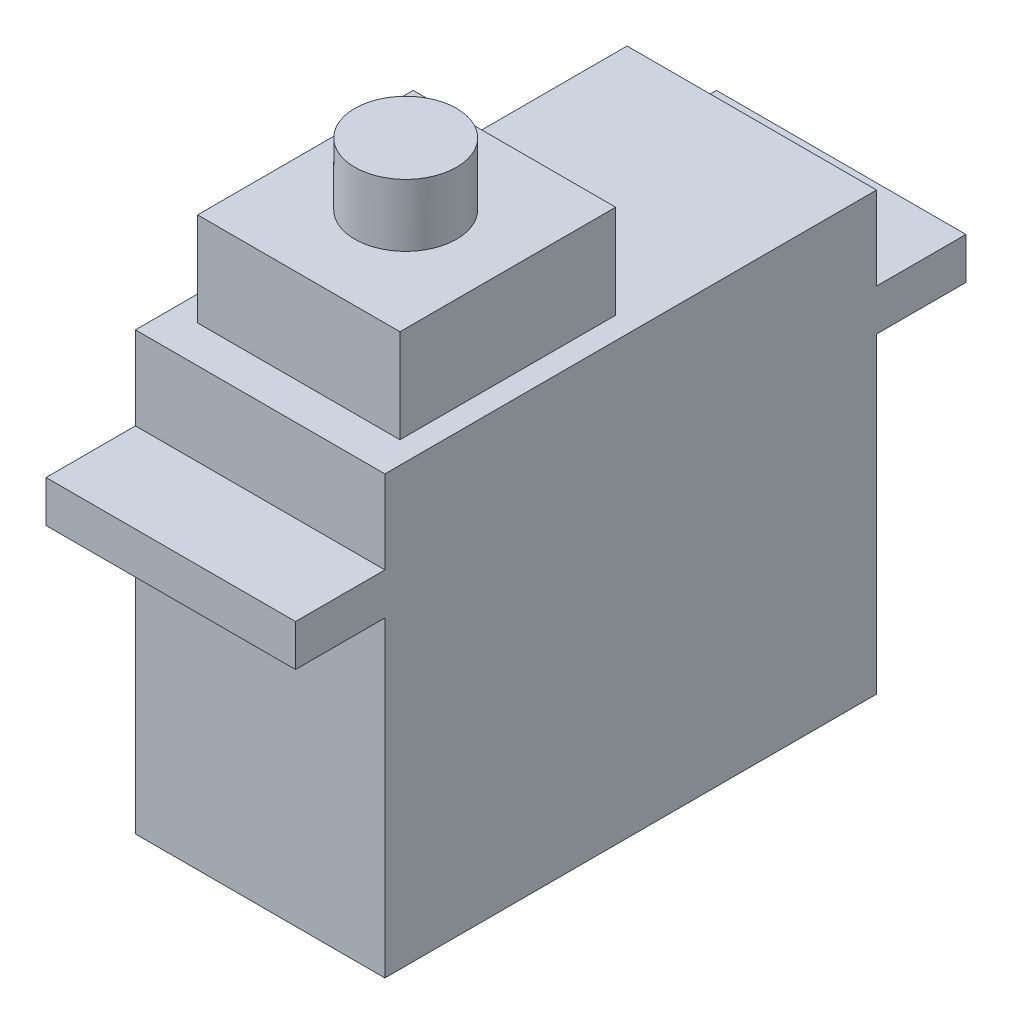
SolidWorks part; units mm, degrees
ref_plane "Front Plane" through (0, 0, 0) normal (0, 0, 1) x (1, 0, 0)
ref_plane "Top Plane" through (0, 0, 0) normal (0, 1, 0) x (1, 0, 0)
ref_plane "Right Plane" through (0, 0, 0) normal (1, 0, 0) x (0, 0, -1)
sketch "Sketch1" plane through (0, 0, 0) normal (1, 0, 0) x (0, 0, -1)
  line L0 (-11.825, 6.5) -> (-11.825, 10.5)
  line L1 (-11.825, -10.5) -> (11.825, -10.5)
  line L2 (-11.825, -10.5) -> (-11.825, 4.5)
  line L3 (-11.825, 10.5) -> (11.825, 10.5)
  line L4 (11.825, -10.5) -> (11.825, 4.5)
  line L5 (-11.825, -10.5) -> (11.825, 10.5) construction
  line L6 (-11.825, 10.5) -> (11.825, -10.5) construction
  line L7 (-16.125, 4.5) -> (-11.825, 4.5)
  line L8 (-16.125, 4.5) -> (-16.125, 6.5)
  line L9 (-16.125, 6.5) -> (-11.825, 6.5)
  line L10 (16.125, 4.5) -> (16.125, 6.5)
  line L11 (-16.125, 4.5) -> (16.125, 6.5) construction
  line L12 (-16.125, 6.5) -> (16.125, 4.5) construction
  line L13 (11.825, 6.5) -> (11.825, 10.5)
  line L14 (11.825, 4.5) -> (16.125, 4.5)
  line L15 (11.825, 6.5) -> (16.125, 6.5)
  point P0 (0, 0)
  point P6 (0, 5.5)
  dimension "D1" = 21
  dimension "D2" = 23.65
  dimension "D3" = 2
  dimension "D4" = 4
  dimension "D5" = 4.3
  dimension "D6" = 4.3
extrude "Boss-Extrude1" add sketch "Sketch1" along normal mid plane 12
sketch "Sketch2" plane through (0, 10.5, 0) normal (0, 1, 0) x (1, 0, 0)
  line L1 (-4.7955, -10.041) -> (4.94, -10.041)
  line L2 (-4.7955, -10.041) -> (-4.7955, 0.3332)
  line L3 (-4.7955, 0.3332) -> (4.94, 0.3332)
  line L4 (4.94, -10.041) -> (4.94, 0.3332)
extrude "Boss-Extrude2" add sketch "Sketch2" along normal blind 8.5 from surface at -4 starting at face at (0, 6.5, 13.975)
sketch "Sketch3" plane through (0, 10.5, 0) normal (0, 1, 0) x (1, 0, 0)
  line L0 (6, -11.825) -> (-6, -11.825) construction
  circle A0 centre (0, -4.825) radius 2.45
  dimension "D1" = 4.9
  dimension "D2" = 7
extrude "Boss-Extrude3" add sketch "Sketch3" along normal blind 7.5
